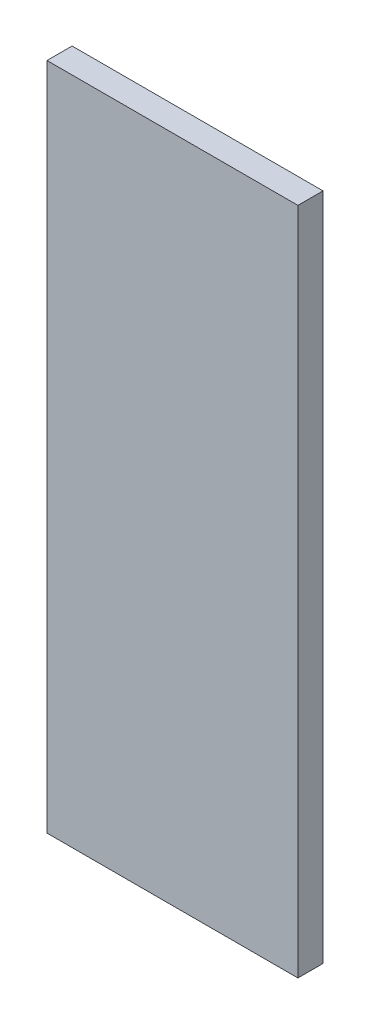
SolidWorks part; units mm, degrees
ref_plane "前视基准面" through (0, 0, 0) normal (0, 0, 1) x (1, 0, 0)
ref_plane "上视基准面" through (0, 0, 0) normal (0, 1, 0) x (1, 0, 0)
ref_plane "右视基准面" through (0, 0, 0) normal (1, 0, 0) x (0, 0, -1)
sketch "草图1" plane through (0, 0, 0) normal (0, 0, 1) x (1, 0, 0)
  line L1 (-12.2034, 140.678) -> (17.7966, 140.678)
  line L2 (-12.2034, 140.678) -> (-12.2034, 60.678)
  line L3 (-12.2034, 60.678) -> (17.7966, 60.678)
  line L4 (17.7966, 140.678) -> (17.7966, 60.678)
  line L5 (-12.2034, 140.678) -> (17.7966, 60.678) construction
  line L6 (-12.2034, 60.678) -> (17.7966, 140.678) construction
  point P0 (2.7966, 100.678)
  dimension "D1" = 80
  dimension "D2" = 30
extrude "凸台-拉伸1" add sketch "草图1" along normal blind 3
